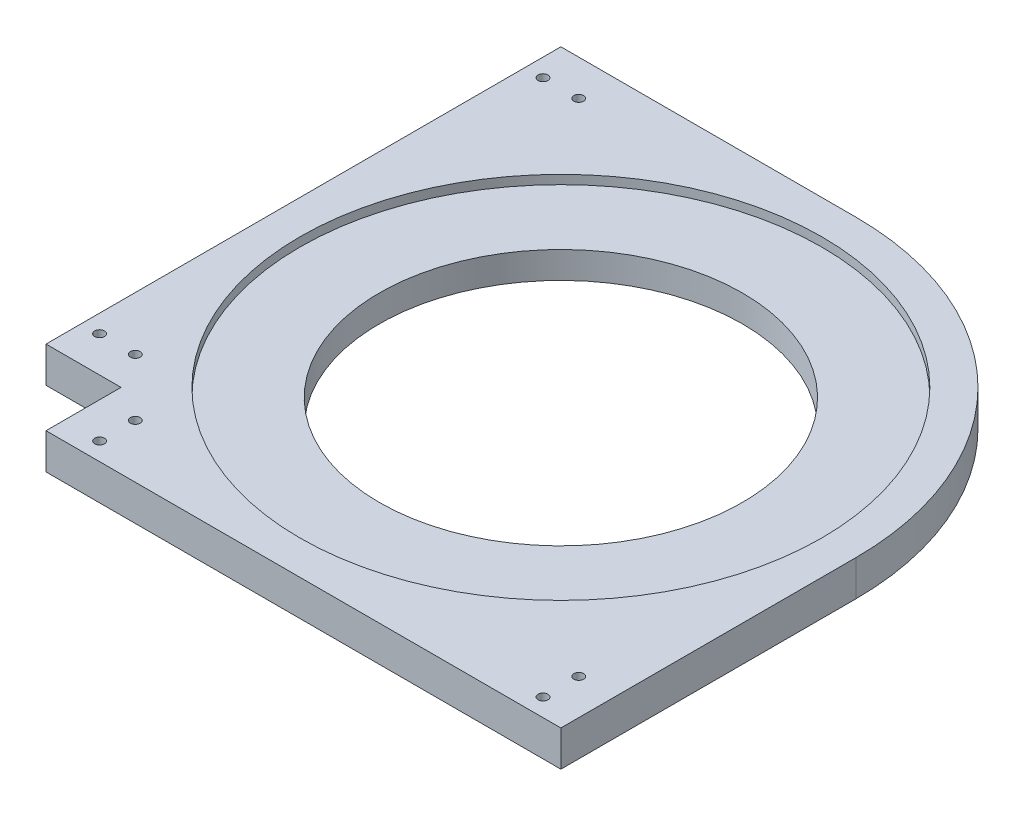
SolidWorks part; units mm, degrees
ref_plane "Front" through (0, 0, 0) normal (0, 0, 1) x (1, 0, 0)
ref_plane "Top" through (0, 0, 0) normal (0, 1, 0) x (1, 0, 0)
ref_plane "Right" through (0, 0, 0) normal (1, 0, 0) x (0, 0, -1)
sketch "Sketch1" plane through (0, 0, 0) normal (0, 1, 0) x (1, 0, 0)
  line L0 (165.1, 0) -> (165.1, -165.1)
  line L1 (165.1, -165.1) -> (-165.1, -165.1)
  line L2 (-165.1, -165.1) -> (-165.1, 165.1)
  line L3 (-165.1, 165.1) -> (0, 165.1)
  line L4 (0, -165.1) -> (-165.1, -165.1) construction
  line L5 (-165.1, 0) -> (-165.1, -165.1) construction
  arc A0 (165.1, 0) -> (0, 165.1) centre (0, 0) ccw
  circle A1 centre (0, 0) radius 165.1 construction
  dimension "D1" = 330.2
  dimension "D2" = 0
  dimension "D3" = 0
extrude "Boss-Extrude1" add sketch "Sketch1" along normal blind 20
sketch "Sketch2" plane through (0, 20, 0) normal (0, 1, 0) x (1, 0, 0)
  circle A0 centre (0, 0) radius 146.05
  dimension "D1" = 292.1
extrude "Cut-Extrude1" cut sketch "Sketch2" against normal blind 5
sketch "Sketch3" plane through (0, 15, 0) normal (0, 1, 0) x (1, 0, 0)
  circle A0 centre (0, 0) radius 101.6
  dimension "D1" = 203.2
extrude "Cut-Extrude2" cut sketch "Sketch3" against normal up to next
sketch "Sketch4" plane through (0, 20, 0) normal (0, 1, 0) x (1, 0, 0)
  line L1 (-165.1, -165.1) -> (-123.1, -165.1)
  line L2 (-165.1, -165.1) -> (-165.1, -123.1)
  line L3 (-165.1, -123.1) -> (-123.1, -123.1)
  line L4 (-123.1, -165.1) -> (-123.1, -123.1)
  line L5 (-165.1, -165.1) -> (-123.1, -123.1) construction
  line L6 (-165.1, -123.1) -> (-123.1, -165.1) construction
  point P4 (-144.1, -144.1)
  dimension "D1" = 42
  dimension "D2" = 42
extrude "Cut-Extrude3" cut sketch "Sketch4" against normal up to next
sketch "Sketch5" plane through (0, 20, 0) normal (0, 1, 0) x (1, 0, 0)
  line L0 (-103.1, -135.1) -> (-103.1, -155.1) construction
  line L1 (145.1, -135.1) -> (145.1, -155.1) construction
  line L2 (-123.1, -165.1) -> (165.1, -165.1) construction
  line L3 (-123.1, -165.1) -> (-123.1, -123.1) construction
  line L4 (165.1, -165.1) -> (165.1, 0) construction
  line L5 (-123.1, -123.1) -> (0, 0) construction
  line L6 (-135.1, 145.1) -> (-155.1, 145.1) construction
  line L7 (-135.1, -103.1) -> (-155.1, -103.1) construction
  circle A0 centre (-103.1, -135.1) radius 2.75
  circle A1 centre (145.1, -135.1) radius 2.75
  circle A2 centre (-103.1, -155.1) radius 2.75
  circle A3 centre (145.1, -155.1) radius 2.75
  circle A4 centre (-155.1, 145.1) radius 2.75
  circle A5 centre (-155.1, -103.1) radius 2.75
  circle A6 centre (-135.1, 145.1) radius 2.75
  circle A7 centre (-135.1, -103.1) radius 2.75
  dimension "D1" = 5.5
  dimension "D2" = 10
  dimension "D5" = 10
  dimension "D3" = 20
  dimension "D4" = 20
  dimension "D6" = 20
  dimension "D7" = 20
extrude "Cut-Extrude4" cut sketch "Sketch5" against normal up to next
